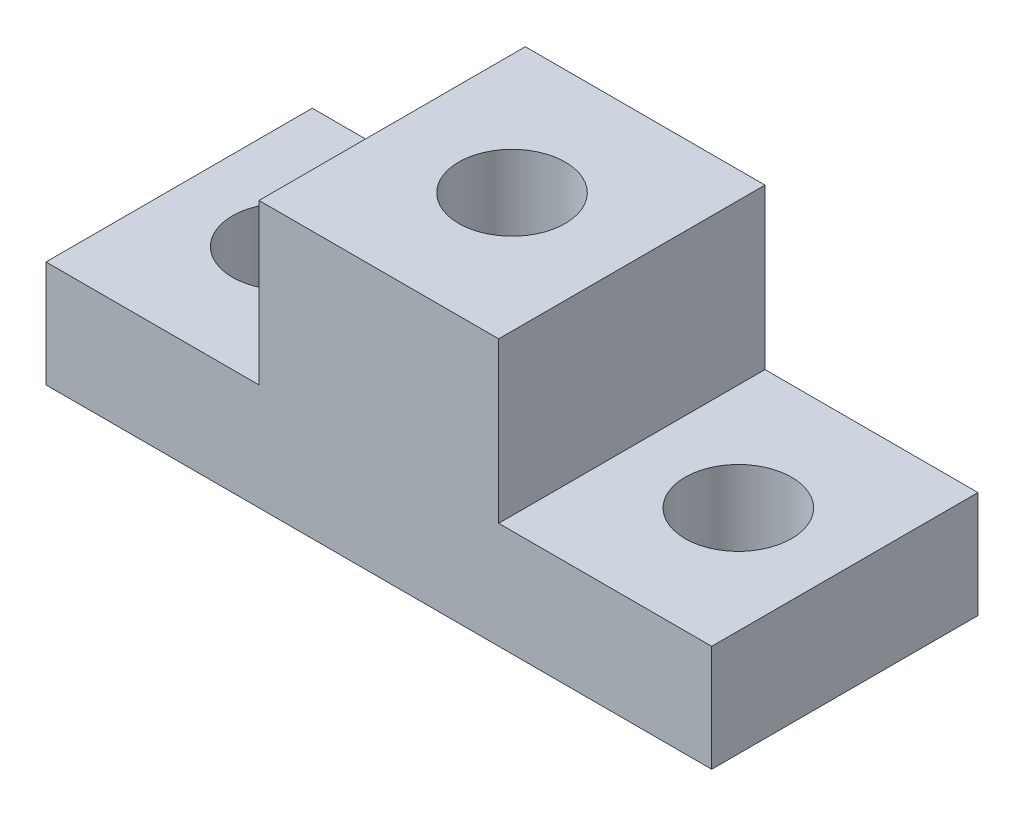
SolidWorks part; units mm, degrees
ref_plane "Front Plane" through (0, 0, 0) normal (0, 0, 1) x (1, 0, 0)
ref_plane "Top Plane" through (0, 0, 0) normal (0, 1, 0) x (1, 0, 0)
ref_plane "Right Plane" through (0, 0, 0) normal (1, 0, 0) x (0, 0, -1)
sketch "Sketch1" plane through (0, 0, 0) normal (0, 1, 0) x (1, 0, 0)
  line L1 (-12.5, 5) -> (12.5, 5)
  line L2 (-12.5, 5) -> (-12.5, -5)
  line L3 (-12.5, -5) -> (12.5, -5)
  line L4 (12.5, 5) -> (12.5, -5)
  line L5 (-12.5, 5) -> (12.5, -5) construction
  line L6 (-12.5, -5) -> (12.5, 5) construction
  point P0 (0, 0)
extrude "Boss-Extrude1" add sketch "Sketch1" along normal blind 10
sketch "Sketch2" plane through (0, 0, 5) normal (0, 0, 1) x (1, 0, 0)
  line L0 (0, 0) -> (0, 12.2436) construction
  line L1 (-12.5, 4) -> (-4.5, 4)
  line L2 (-12.5, 10) -> (-12.5, 0) construction
  line L3 (-4.5, 4) -> (-4.5, 10)
  line L4 (-12.5, 10) -> (12.5, 10) construction
  line L5 (-12.5, 0) -> (12.5, 0) construction
  line L6 (-12.5, 4) -> (-12.5, 10)
  line L7 (-12.5, 10) -> (-4.5, 10)
  line L8 (12.5, 10) -> (4.5, 10)
  line L9 (12.5, 4) -> (12.5, 10)
  line L10 (4.5, 4) -> (4.5, 10)
  line L11 (12.5, 4) -> (4.5, 4)
  dimension "D1" = 4
extrude "Cut-Extrude1" cut sketch "Sketch2" against normal blind 10
sketch "Sketch3" plane through (0, 10, 0) normal (0, 1, 0) x (1, 0, 0)
  circle A0 centre (0, 0) radius 2
extrude "Cut-Extrude2" cut sketch "Sketch3" against normal through all
sketch "Sketch4" plane through (0, 4, 0) normal (0, 1, 0) x (1, 0, 0)
  circle A0 centre (-8.5, 0) radius 2
  circle A1 centre (8.5, 0) radius 2
extrude "Cut-Extrude3" cut sketch "Sketch4" against normal blind 10
